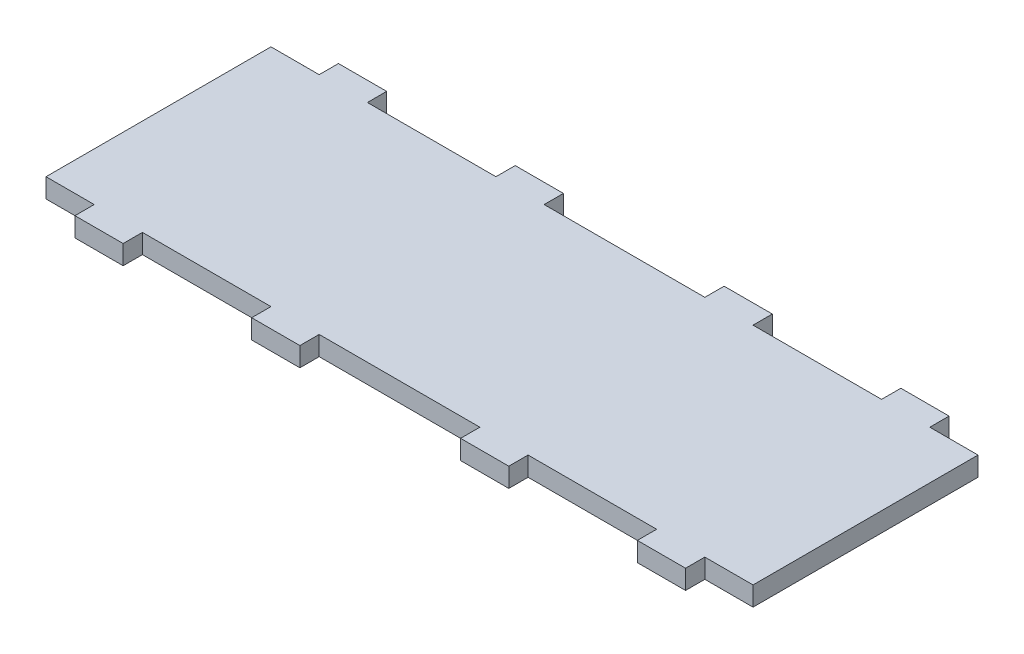
SolidWorks part; units mm, degrees
material "Acrylic (Medium-high impact)"
ref_plane "Front Plane" through (0, 0, 0) normal (0, 0, 1) x (1, 0, 0)
ref_plane "Top Plane" through (0, 0, 0) normal (0, 1, 0) x (1, 0, 0)
ref_plane "Right Plane" through (0, 0, 0) normal (1, 0, 0) x (0, 0, -1)
sketch "Sketch1" plane through (0, 0, 0) normal (0, 1, 0) x (1, 0, 0)
  line L0 (-160.3867, 70) -> (-145.3867, 70)
  line L1 (-365.3867, 70) -> (-350.3867, 70)
  line L2 (-365.3867, 70) -> (-365.3867, 0)
  line L3 (-365.3867, 0) -> (-350.3867, 0)
  line L4 (-145.3867, 70) -> (-145.3867, 0)
  line L6 (-350.3867, 70) -> (-350.3867, 76)
  line L7 (-350.3867, 76) -> (-335.3867, 76)
  line L8 (-335.3867, 70) -> (-335.3867, 76)
  line L10 (-295.3867, 70) -> (-295.3867, 76)
  line L11 (-295.3867, 76) -> (-280.3867, 76)
  line L12 (-280.3867, 70) -> (-280.3867, 76)
  line L14 (-175.3867, 70) -> (-175.3867, 76)
  line L15 (-175.3867, 76) -> (-160.3867, 76)
  line L16 (-160.3867, 70) -> (-160.3867, 76)
  line L17 (-280.3867, 70) -> (-230.3867, 70)
  line L18 (-335.3867, 70) -> (-295.3867, 70)
  line L19 (-365.3867, -6) -> (-350.3867, -6) construction
  line L21 (-350.3867, 0) -> (-350.3867, -6)
  line L22 (-350.3867, -6) -> (-335.3867, -6)
  line L23 (-335.3867, 0) -> (-335.3867, -6)
  line L25 (-295.3867, 0) -> (-295.3867, -6)
  line L26 (-295.3867, -6) -> (-280.3867, -6)
  line L27 (-280.3867, 0) -> (-280.3867, -6)
  line L29 (-175.3867, 0) -> (-175.3867, -6)
  line L30 (-175.3867, -6) -> (-160.3867, -6)
  line L31 (-160.3867, 0) -> (-160.3867, -6)
  line L32 (-335.3867, 0) -> (-295.3867, 0)
  line L33 (-280.3867, 0) -> (-230.3867, 0)
  line L34 (-160.3867, 0) -> (-145.3867, 0)
  line L35 (-215.3867, 0) -> (-175.3867, 0)
  line L37 (-230.3867, 0) -> (-230.3867, -6)
  line L38 (-230.3867, -6) -> (-215.3867, -6)
  line L39 (-215.3867, 0) -> (-215.3867, -6)
  line L40 (-215.3867, 70) -> (-175.3867, 70)
  line L42 (-230.3867, 70) -> (-230.3867, 76)
  line L43 (-230.3867, 76) -> (-215.3867, 76)
  line L44 (-215.3867, 70) -> (-215.3867, 76)
  point P34 (-255.3867, 0)
  dimension "D1" = 70
  dimension "D2" = 220
  dimension "D3" = 6
  dimension "D4" = 6
  dimension "D5" = 6
  dimension "D6" = 15
  dimension "D7" = 15
  dimension "D8" = 15
  dimension "D9" = 15
  dimension "D10" = 15
  dimension "D11" = 15
  dimension "D12" = 6
  dimension "D13" = 6
  dimension "D14" = 6
  dimension "D15" = 15
  dimension "D16" = 50
  dimension "D17" = 110
  dimension "D18" = 0
extrude "Boss-Extrude1" add sketch "Sketch1" along normal blind 6
